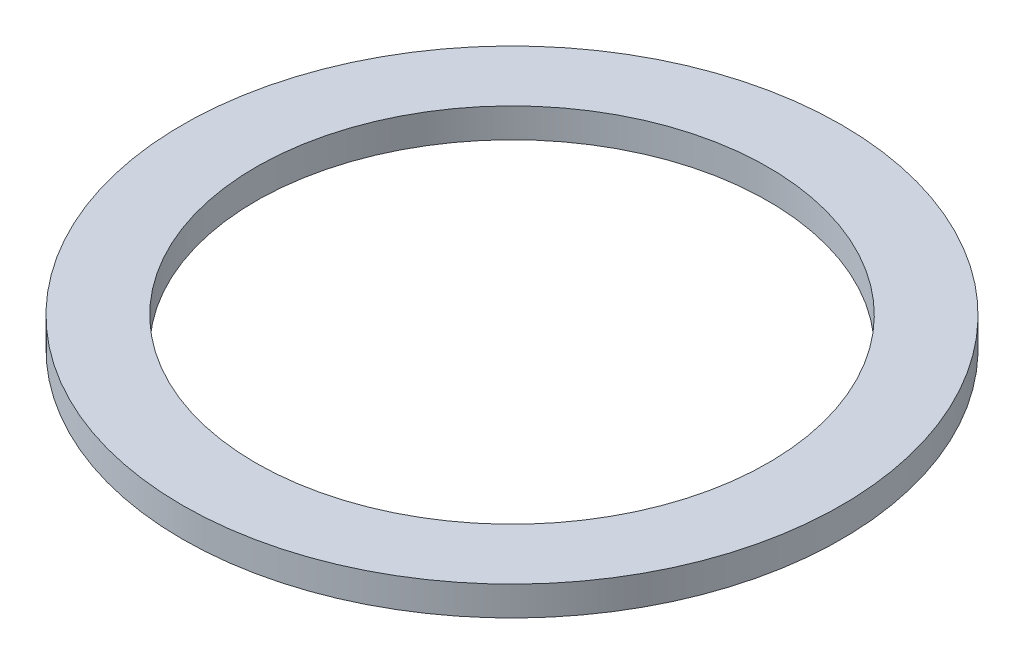
SolidWorks part; units mm, degrees
ref_plane "Front Plane" through (0, 0, 0) normal (0, 0, 1) x (1, 0, 0)
ref_plane "Top Plane" through (0, 0, 0) normal (0, 1, 0) x (1, 0, 0)
ref_plane "Right Plane" through (0, 0, 0) normal (1, 0, 0) x (0, 0, -1)
sketch "Sketch1" plane through (0, 0, 0) normal (0, 1, 0) x (1, 0, 0)
  circle A0 centre (0, 0) radius 17.46
  circle A1 centre (0, 0) radius 22.46
  dimension "D1" = 34.92
  dimension "D2" = 5
extrude "Boss-Extrude1" add sketch "Sketch1" along normal blind 2
